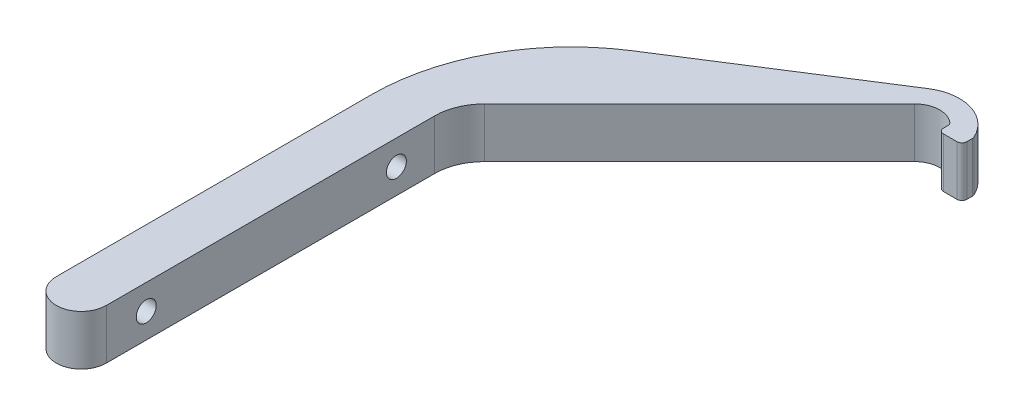
SolidWorks part; units mm, degrees
material "ABS"
ref_plane "Front Plane" through (0, 0, 0) normal (0, 0, 1) x (1, 0, 0)
ref_plane "Top Plane" through (0, 0, 0) normal (0, 1, 0) x (1, 0, 0)
ref_plane "Right Plane" through (0, 0, 0) normal (1, 0, 0) x (0, 0, -1)
other "Center of Mass"
sketch "Sketch1" plane through (0, 0, 0) normal (0, 1, 0) x (1, 0, 0)
  line L0 (0, 0) -> (0, 53.0552)
  line L2 (10, -0.138) -> (10, 55.7199)
  line L3 (12.9289, 62.791) -> (55.9619, 105.824)
  line L9 (54.687, 109.8394) -> (18.508, 86.7909)
  line L16 (0, 0) -> (0, -10)
  line L17 (10, -0.138) -> (10, -10)
  line L21 (63.033, 105.3821) -> (63.033, 104.5044)
  line L22 (64.033, 103.5044) -> (66.723, 103.5044)
  line L23 (67.723, 104.5044) -> (67.723, 105.6118)
  arc A1 (0, 53.0552) -> (18.508, 86.7909) centre (40, 53.0552) cw
  arc A6 (10, 55.7199) -> (12.9289, 62.791) centre (20, 55.7199) cw
  arc A11 (10, -10) -> (0, -10) centre (5, -10) cw
  arc A14 (55.9619, 105.824) -> (62.6669, 106.1556) centre (59.4975, 102.2884) cw
  arc A15 (54.687, 109.8394) -> (67.6315, 106.0296) centre (59.4975, 102.2884) cw
  arc A16 (67.6315, 106.0296) -> (67.723, 105.6118) centre (66.723, 105.6118) cw
  arc A17 (62.6669, 106.1556) -> (63.033, 105.3821) centre (62.033, 105.3821) cw
  arc A18 (63.033, 104.5044) -> (64.033, 103.5044) centre (64.033, 104.5044) ccw
  arc A19 (66.723, 103.5044) -> (67.723, 104.5044) centre (66.723, 104.5044) ccw
  point P7 (0, 0)
  point P13 (10.4219, 60.4675)
  point P16 (0, 75)
  point P21 (67.723, 105.824)
  point P24 (63.033, 105.824)
  point P28 (10, 59.862)
  point P31 (0, -10)
  point P34 (10, -10)
  dimension "D4" = 1
  dimension "D5" = 40
  dimension "D6" = 1
  dimension "D7" = 65
  dimension "D8" = 135
  dimension "D11" = 60
  dimension "D16" = 10
  dimension "D12" = 5
  dimension "D2" = 5
  dimension "D1" = 75
  dimension "D3" = 10
  dimension "D10" = 122.5
  dimension "D13" = 10
extrude "Boss-Extrude1" add sketch "Sketch1" along normal blind 10
sketch "Sketch4" plane through (0, 0, 0) normal (-1, 0, 0) x (0, 0, 1)
  line L0 (-53.0552, 10) -> (10, 10) construction
  line L1 (10, 10) -> (10, 0) construction
  line L2 (-53.0552, 10) -> (-53.0552, 0) construction
  circle A0 centre (-48.0552, 5) radius 2
  circle A1 centre (2, 5) radius 2
  point P4 (0, 0)
  dimension "D1" = 4
  dimension "D2" = 4
  dimension "D3" = 5
  dimension "D4" = 8
  dimension "D5" = 5
extrude "Cut-Extrude3" cut sketch "Sketch4" against normal blind 10
